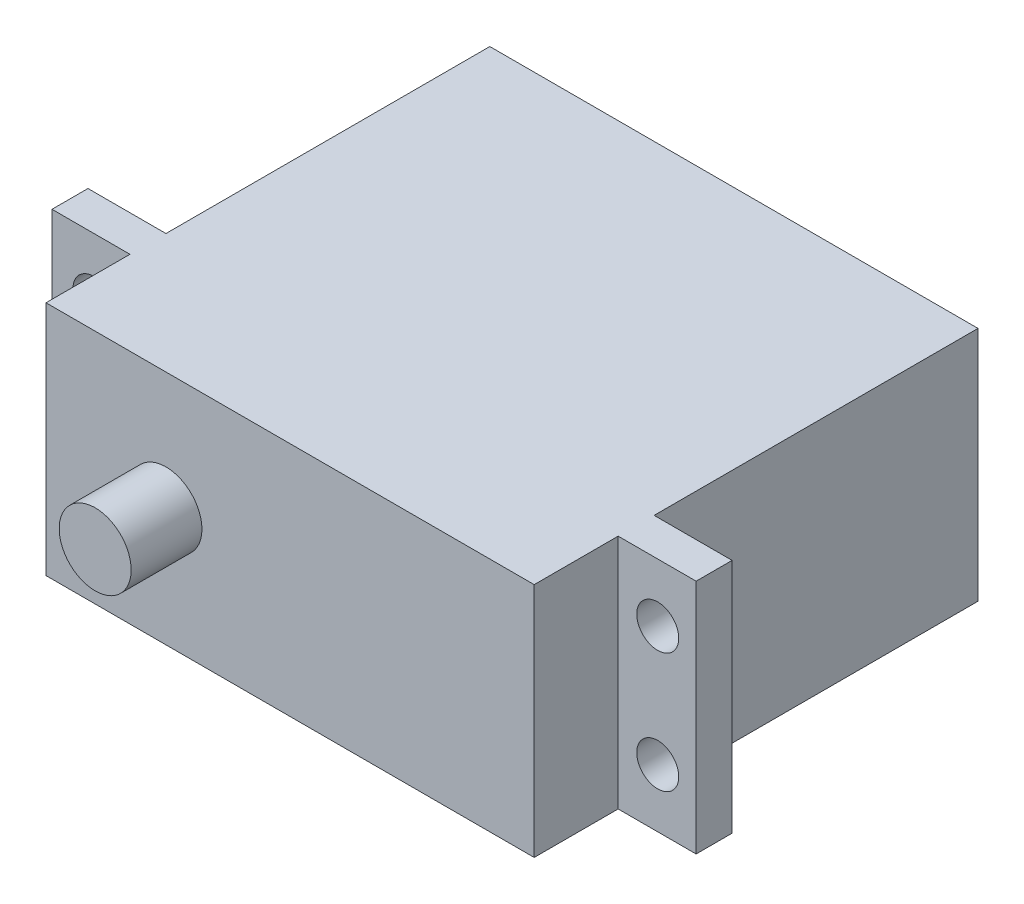
SolidWorks part; units mm, degrees
ref_plane "Front Plane" through (0, 0, 0) normal (0, 0, 1) x (1, 0, 0)
ref_plane "Top Plane" through (0, 0, 0) normal (0, 1, 0) x (1, 0, 0)
ref_plane "Right Plane" through (0, 0, 0) normal (1, 0, 0) x (0, 0, -1)
sketch "Case_40p7x19p7_profile" plane through (0, 0, 0) normal (0, 0, 1) x (1, 0, 0)
  line L1 (-10, -9.85) -> (30.7, -9.85)
  line L2 (-10, -9.85) -> (-10, 9.85)
  line L3 (-10, 9.85) -> (30.7, 9.85)
  line L4 (30.7, -9.85) -> (30.7, 9.85)
extrude "Case_40p7x19p7" add sketch "Case_40p7x19p7_profile" along normal blind 37 from offset 30
sketch "Mounting_flange_nominal_profile" plane through (0, 0, 0) normal (0, 0, 1) x (1, 0, 0)
  line L1 (-16.5, -9.85) -> (37.2, -9.85)
  line L2 (-16.5, -9.85) -> (-16.5, 9.85)
  line L3 (-16.5, 9.85) -> (37.2, 9.85)
  line L4 (37.2, -9.85) -> (37.2, 9.85)
extrude "Mounting_flange_nominal" add sketch "Mounting_flange_nominal_profile" along normal blind 3 from offset 3
sketch "Output_envelope_not_spline_profile" plane through (0, 0, 0) normal (0, 0, 1) x (1, 0, 0)
  circle A0 centre (0, 0) radius 3
extrude "Output_envelope_not_spline" add sketch "Output_envelope_not_spline_profile" along normal blind 5.9 from offset 7
sketch "Tab_holes_nominal_profile" plane through (0, 0, 0) normal (0, 0, 1) x (1, 0, 0)
  circle A0 centre (-13, 5) radius 1.75
  circle A1 centre (-13, -5) radius 1.75
  circle A2 centre (34, 5) radius 1.75
  circle A3 centre (34, -5) radius 1.75
extrude "Tab_holes_nominal" cut sketch "Tab_holes_nominal_profile" along normal through all from offset 50
